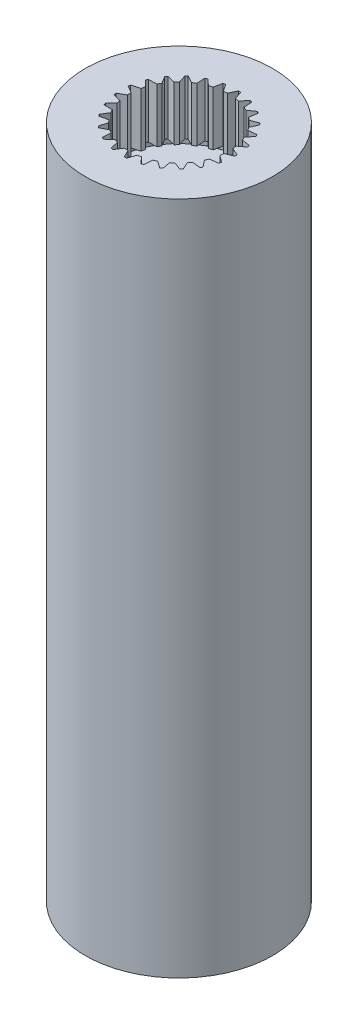
SolidWorks part; units mm, degrees
ref_plane "Front" through (0, 0, 0) normal (0, 0, 1) x (1, 0, 0)
ref_plane "Top" through (0, 0, 0) normal (0, 1, 0) x (1, 0, 0)
ref_plane "Right" through (0, 0, 0) normal (1, 0, 0) x (0, 0, -1)
sketch "Sketch1" plane through (0, 0, 0) normal (0, 0, 1) x (1, 0, 0)
  line L0 (5, 34.5) -> (0, 34.5)
  line L1 (0, 34.5) -> (0, -1.5)
  line L2 (0, -1.5) -> (5, -1.5)
  line L3 (5, -1.5) -> (5, 34.5)
  line L4 (0, 34.5) -> (0, -1.5) construction
revolve "Revolve1" add sketch "Sketch1" angle 360 about L4
ref_plane "Plane1" through (0, 31.6, 0) normal (0, 1, 0) x (1, 0, 0)
sketch "Sketch2" plane through (0, 31.6, 0) normal (0, 1, 0) x (1, 0, 0)
  circle A0 centre (0, 0) radius 3.4315
extrude "Cut-Extrude1" cut sketch "Sketch2" against normal blind 0.5
sketch "Sketch3" plane through (0, -1.5, 0) normal (0, -1, 0) x (1, 0, 0)
  circle A0 centre (0, 0) radius 3.5
extrude "Cut-Extrude2" cut sketch "Sketch3" against normal blind 31.5
sketch "Sketch4" plane through (0, 30, 0) normal (0, -1, 0) x (1, 0, 0)
  circle A0 centre (0, 0) radius 1.5
extrude "Cut-Extrude3" cut sketch "Sketch4" against normal up to next
sketch "Sketch5" plane through (0, 34.5, 0) normal (0, 1, 0) x (-1, 0, 0)
  line L0 (2.4303, 1.8428) -> (1.9993, 1.7394)
  line L1 (1.8615, 1.8861) -> (1.9918, 2.3098)
  line L2 (1.8957, 2.3893) -> (1.5039, 2.1819)
  line L3 (1.3339, 2.2898) -> (1.3548, 2.7326)
  line L4 (1.2419, 2.7857) -> (0.914, 2.4874)
  line L5 (0.7226, 2.5496) -> (0.6327, 2.9837)
  line L6 (0.5101, 3.007) -> (0.2667, 2.6365)
  line L7 (0.0658, 2.6492) -> (-0.1292, 3.0473)
  line L8 (-0.2537, 3.0394) -> (-0.3973, 2.62)
  line L9 (-0.5951, 2.5823) -> (-0.883, 2.9194)
  line L10 (-1.0016, 2.8808) -> (-1.0364, 2.4389)
  line L11 (-1.2186, 2.3532) -> (-1.5812, 2.6081)
  line L12 (-1.6866, 2.5412) -> (-1.6104, 2.1045)
  line L13 (-1.7655, 1.9762) -> (-2.1802, 2.1329)
  line L14 (-2.2656, 2.0419) -> (-2.0832, 1.6379)
  line L15 (-2.2015, 1.4751) -> (-2.6421, 1.5237)
  line L16 (-2.7022, 1.4144) -> (-2.4251, 1.0684)
  line L17 (-2.4992, 0.8812) -> (-2.938, 0.8188)
  line L18 (-2.9691, 0.6979) -> (-2.6146, 0.4318)
  line L19 (-2.6398, 0.232) -> (-3.0494, 0.0624)
  line L20 (-3.0494, -0.0624) -> (-2.6398, -0.232)
  line L21 (-2.6146, -0.4318) -> (-2.9691, -0.6979)
  line L22 (-2.938, -0.8188) -> (-2.4992, -0.8812)
  line L23 (-2.4251, -1.0684) -> (-2.7022, -1.4144)
  line L24 (-2.6421, -1.5237) -> (-2.2015, -1.4751)
  line L25 (-2.0832, -1.6379) -> (-2.2656, -2.0419)
  line L26 (-2.1802, -2.1329) -> (-1.7655, -1.9762)
  line L27 (-1.6104, -2.1045) -> (-1.6866, -2.5412)
  line L28 (-1.5812, -2.6081) -> (-1.2186, -2.3532)
  line L29 (-1.0364, -2.4389) -> (-1.0016, -2.8808)
  line L30 (-0.883, -2.9194) -> (-0.5951, -2.5823)
  line L31 (-0.3973, -2.62) -> (-0.2537, -3.0394)
  line L32 (-0.1292, -3.0473) -> (0.0658, -2.6492)
  line L33 (0.2667, -2.6365) -> (0.5101, -3.007)
  line L34 (0.6327, -2.9837) -> (0.7226, -2.5496)
  line L35 (0.914, -2.4874) -> (1.2419, -2.7857)
  line L36 (1.3548, -2.7326) -> (1.3339, -2.2898)
  line L37 (1.5039, -2.1819) -> (1.8957, -2.3893)
  line L38 (1.9918, -2.3098) -> (1.8615, -1.8861)
  line L39 (1.9993, -1.7394) -> (2.4303, -1.8428)
  line L40 (2.5037, -1.7419) -> (2.272, -1.3639)
  line L41 (2.369, -1.1875) -> (2.8123, -1.1806)
  line L42 (2.8582, -1.0645) -> (2.5399, -0.756)
  line L43 (2.5899, -0.5611) -> (3.0175, -0.4441)
  line L44 (3.0331, -0.3203) -> (2.6481, -0.1007)
  line L45 (2.6481, 0.1007) -> (3.0331, 0.3203)
  line L46 (3.0175, 0.4441) -> (2.5899, 0.5611)
  line L47 (2.5399, 0.756) -> (2.8582, 1.0645)
  line L48 (2.8123, 1.1806) -> (2.369, 1.1875)
  line L49 (2.272, 1.3639) -> (2.5037, 1.7419)
  arc A0 (2.5037, 1.7419) -> (2.4303, 1.8428) centre (0, 0) ccw
  arc A1 (1.9993, 1.7394) -> (1.8615, 1.8861) centre (0, 0) ccw
  arc A2 (1.9918, 2.3098) -> (1.8957, 2.3893) centre (0, 0) ccw
  arc A3 (1.5039, 2.1819) -> (1.3339, 2.2898) centre (0, 0) ccw
  arc A4 (1.3548, 2.7326) -> (1.2419, 2.7857) centre (0, 0) ccw
  arc A5 (0.914, 2.4874) -> (0.7226, 2.5496) centre (0, 0) ccw
  arc A6 (0.6327, 2.9837) -> (0.5101, 3.007) centre (0, 0) ccw
  arc A7 (0.2667, 2.6365) -> (0.0658, 2.6492) centre (0, 0) ccw
  arc A8 (-0.1292, 3.0473) -> (-0.2537, 3.0394) centre (0, 0) ccw
  arc A9 (-0.3973, 2.62) -> (-0.5951, 2.5823) centre (0, 0) ccw
  arc A10 (-0.883, 2.9194) -> (-1.0016, 2.8808) centre (0, 0) ccw
  arc A11 (-1.0364, 2.4389) -> (-1.2186, 2.3532) centre (0, 0) ccw
  arc A12 (-1.5812, 2.6081) -> (-1.6866, 2.5412) centre (0, 0) ccw
  arc A13 (-1.6104, 2.1045) -> (-1.7655, 1.9762) centre (0, 0) ccw
  arc A14 (-2.1802, 2.1329) -> (-2.2656, 2.0419) centre (0, 0) ccw
  arc A15 (-2.0832, 1.6379) -> (-2.2015, 1.4751) centre (0, 0) ccw
  arc A16 (-2.6421, 1.5237) -> (-2.7022, 1.4144) centre (0, 0) ccw
  arc A17 (-2.4251, 1.0684) -> (-2.4992, 0.8812) centre (0, 0) ccw
  arc A18 (-2.938, 0.8188) -> (-2.9691, 0.6979) centre (0, 0) ccw
  arc A19 (-2.6146, 0.4318) -> (-2.6398, 0.232) centre (0, 0) ccw
  arc A20 (-3.0494, 0.0624) -> (-3.0494, -0.0624) centre (0, 0) ccw
  arc A21 (-2.6398, -0.232) -> (-2.6146, -0.4318) centre (0, 0) ccw
  arc A22 (-2.9691, -0.6979) -> (-2.938, -0.8188) centre (0, 0) ccw
  arc A23 (-2.4992, -0.8812) -> (-2.4251, -1.0684) centre (0, 0) ccw
  arc A24 (-2.7022, -1.4144) -> (-2.6421, -1.5237) centre (0, 0) ccw
  arc A25 (-2.2015, -1.4751) -> (-2.0832, -1.6379) centre (0, 0) ccw
  arc A26 (-2.2656, -2.0419) -> (-2.1802, -2.1329) centre (0, 0) ccw
  arc A27 (-1.7655, -1.9762) -> (-1.6104, -2.1045) centre (0, 0) ccw
  arc A28 (-1.6866, -2.5412) -> (-1.5812, -2.6081) centre (0, 0) ccw
  arc A29 (-1.2186, -2.3532) -> (-1.0364, -2.4389) centre (0, 0) ccw
  arc A30 (-1.0016, -2.8808) -> (-0.883, -2.9194) centre (0, 0) ccw
  arc A31 (-0.5951, -2.5823) -> (-0.3973, -2.62) centre (0, 0) ccw
  arc A32 (-0.2537, -3.0394) -> (-0.1292, -3.0473) centre (0, 0) ccw
  arc A33 (0.0658, -2.6492) -> (0.2667, -2.6365) centre (0, 0) ccw
  arc A34 (0.5101, -3.007) -> (0.6327, -2.9837) centre (0, 0) ccw
  arc A35 (0.7226, -2.5496) -> (0.914, -2.4874) centre (0, 0) ccw
  arc A36 (1.2419, -2.7857) -> (1.3548, -2.7326) centre (0, 0) ccw
  arc A37 (1.3339, -2.2898) -> (1.5039, -2.1819) centre (0, 0) ccw
  arc A38 (1.8957, -2.3893) -> (1.9918, -2.3098) centre (0, 0) ccw
  arc A39 (1.8615, -1.8861) -> (1.9993, -1.7394) centre (0, 0) ccw
  arc A40 (2.4303, -1.8428) -> (2.5037, -1.7419) centre (0, 0) ccw
  arc A41 (2.272, -1.3639) -> (2.369, -1.1875) centre (0, 0) ccw
  arc A42 (2.8123, -1.1806) -> (2.8582, -1.0645) centre (0, 0) ccw
  arc A43 (2.5399, -0.756) -> (2.5899, -0.5611) centre (0, 0) ccw
  arc A44 (3.0175, -0.4441) -> (3.0331, -0.3203) centre (0, 0) ccw
  arc A45 (2.6481, -0.1007) -> (2.6481, 0.1007) centre (0, 0) ccw
  arc A46 (3.0331, 0.3203) -> (3.0175, 0.4441) centre (0, 0) ccw
  arc A47 (2.5899, 0.5611) -> (2.5399, 0.756) centre (0, 0) ccw
  arc A48 (2.8582, 1.0645) -> (2.8123, 1.1806) centre (0, 0) ccw
  arc A49 (2.369, 1.1875) -> (2.272, 1.3639) centre (0, 0) ccw
extrude "Cut-Extrude4" cut sketch "Sketch5" against normal up to next
